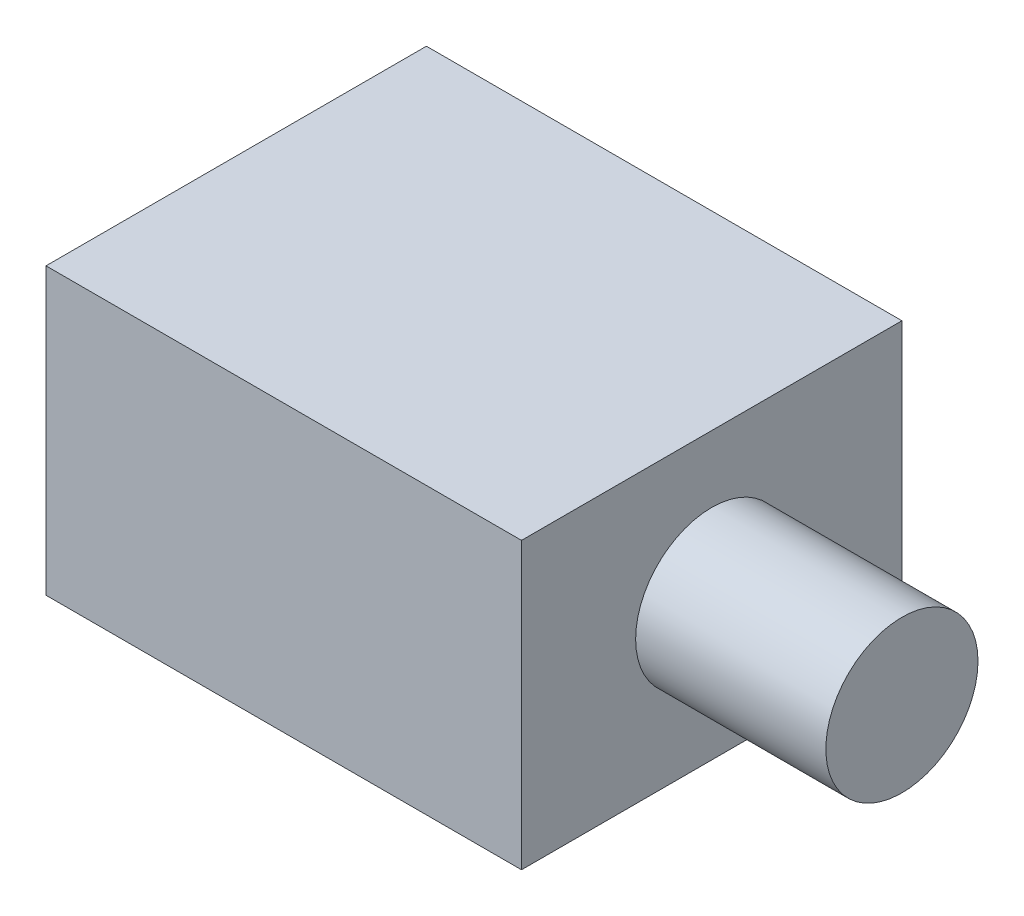
SolidWorks part; units mm, degrees
ref_plane "前视基准面" through (0, 0, 0) normal (0, 0, 1) x (1, 0, 0)
ref_plane "上视基准面" through (0, 0, 0) normal (0, 1, 0) x (1, 0, 0)
ref_plane "右视基准面" through (0, 0, 0) normal (1, 0, 0) x (0, 0, -1)
sketch "草图1" plane through (0, 0, 0) normal (0, 1, 0) x (1, 0, 0)
  line L0 (-25, 20) -> (25, 20)
  line L1 (25, 20) -> (25, -20)
  line L2 (25, -20) -> (-25, -20)
  line L3 (-25, -20) -> (-25, 20)
extrude "凸台-拉伸1" add sketch "草图1" along normal blind 30
ref_plane "基准面1" through (45, 0, 0) normal (1, 0, 0) x (0, 0, -1)
sketch "草图2" plane through (45, 0, 0) normal (1, 0, 0) x (0, 0, -1)
  circle A0 centre (0, 15) radius 8
extrude "凸台-拉伸2" add sketch "草图2" against normal up to body
